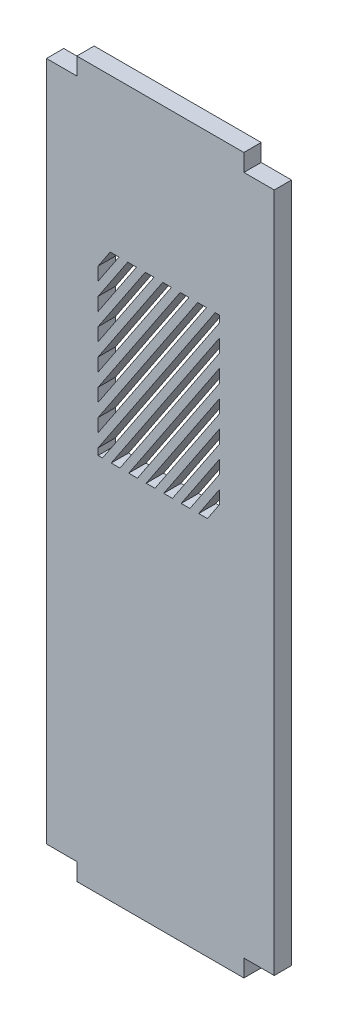
SolidWorks part; units mm, degrees
ref_plane "Front Plane" through (0, 0, 0) normal (0, 0, 1) x (1, 0, 0)
ref_plane "Top Plane" through (0, 0, 0) normal (0, 1, 0) x (1, 0, 0)
ref_plane "Right Plane" through (0, 0, 0) normal (1, 0, 0) x (0, 0, -1)
sketch "Sketch1" plane through (0, 0, 0) normal (0, 0, 1) x (1, 0, 0)
  line L1 (0, 0) -> (75, 0)
  line L2 (0, 0) -> (0, 235.4)
  line L3 (0, 235.4) -> (75, 235.4)
  line L4 (75, 0) -> (75, 235.4)
  dimension "D1" = 235.4
  dimension "D2" = 75
extrude "Boss-Extrude1" add sketch "Sketch1" along normal blind 5.7
sketch "Sketch2" plane through (0, 0, 0) normal (0, 0, -1) x (-1, 0, 0)
  line L2 (-75, 0) -> (-65, 0)
  line L3 (-75, 0) -> (-75, 5.7)
  line L4 (-75, 5.7) -> (-65, 5.7)
  line L6 (-65, 0) -> (-65, 5.7)
  line L7 (0, 0) -> (-10, 0)
  line L8 (0, 0) -> (0, 5.7)
  line L9 (0, 5.7) -> (-10, 5.7)
  line L12 (-10, 0) -> (-10, 5.7)
  line L13 (0, 235.4) -> (-10, 235.4)
  line L14 (0, 235.4) -> (0, 229.7)
  line L15 (0, 229.7) -> (-10, 229.7)
  line L16 (-10, 235.4) -> (-10, 229.7)
  line L17 (-75, 235.4) -> (-65, 235.4)
  line L18 (-75, 235.4) -> (-75, 229.7)
  line L19 (-75, 229.7) -> (-65, 229.7)
  line L20 (-65, 235.4) -> (-65, 229.7)
  dimension "D1" = 5.7
  dimension "D2" = 5.7
  dimension "D3" = 10
  dimension "D4" = 10
  dimension "D5" = 10
  dimension "D6" = 5.7
  dimension "D7" = 5.7
  dimension "D8" = 10
extrude "Cut-Extrude1" cut sketch "Sketch2" against normal blind 5.7
sketch "Sketch3" plane through (0, 0, 5.7) normal (0, 0, 1) x (1, 0, 0)
  line L1 (75, 5.7) -> (75, 229.7) construction
  line L39 (57, 185) -> (17, 125) construction
  line L40 (17, 185) -> (57, 185)
  line L41 (17, 185) -> (17, 125)
  line L42 (17, 125) -> (57, 125)
  line L43 (57, 185) -> (57, 125)
  line L44 (55.5578, 185) -> (17, 127.1633)
  line L45 (57, 182.8367) -> (18.4422, 125)
  line L46 (37, 155) -> (17, 155) construction
  line L47 (37, 155) -> (57, 155) construction
  line L48 (52.6778, 185) -> (17, 131.4833)
  line L49 (49.7978, 185) -> (17, 135.8033)
  line L50 (46.9178, 185) -> (17, 140.1233)
  line L51 (44.0378, 185) -> (17, 144.4433)
  line L52 (41.1578, 185) -> (17, 148.7633)
  line L53 (38.2778, 185) -> (17, 153.0833)
  line L54 (35.3978, 185) -> (17, 157.4033)
  line L55 (32.5178, 185) -> (17, 161.7233)
  line L56 (29.6378, 185) -> (17, 166.0433)
  line L57 (26.7578, 185) -> (17, 170.3633)
  line L58 (23.8778, 185) -> (17, 174.6833)
  line L59 (20.9978, 185) -> (17, 179.0033)
  line L60 (18.1178, 185) -> (17, 183.3233)
  line L61 (57, 178.5167) -> (21.3222, 125)
  line L62 (57, 174.1967) -> (24.2022, 125)
  line L63 (57, 169.8767) -> (27.0822, 125)
  line L64 (57, 165.5567) -> (29.9622, 125)
  line L65 (57, 161.2367) -> (32.8422, 125)
  line L66 (57, 156.9167) -> (35.7222, 125)
  line L67 (57, 152.5967) -> (38.6022, 125)
  line L68 (57, 148.2767) -> (41.4822, 125)
  line L69 (57, 143.9567) -> (44.3622, 125)
  line L70 (57, 139.6367) -> (47.2422, 125)
  line L71 (57, 135.3167) -> (50.1222, 125)
  line L72 (57, 130.9967) -> (53.0022, 125)
  line L73 (57, 126.6767) -> (55.8822, 125)
  line L74 (10, 0) -> (65, 0) construction
  point P79 (35.5578, 155)
  point P82 (38.4422, 155)
  dimension "D7" = 40
  dimension "D8" = 155
  dimension "D9" = 38
  dimension "D10" = 1.2
  dimension "D11" = 2.3963
  dimension "D12" = 2.3963
  dimension "D13" = 2.3963
  dimension "D14" = 2.3963
  dimension "D15" = 2.3963
  dimension "D16" = 2.3963
  dimension "D17" = 2.3963
  dimension "D18" = 2.3963
  dimension "D19" = 2.3963
  dimension "D20" = 2.3963
  dimension "D21" = 2.3963
  dimension "D22" = 2.3963
  dimension "D23" = 2.3963
  dimension "D24" = 2.3963
  dimension "D25" = 2.3963
  dimension "D26" = 2.3963
  dimension "D27" = 2.3963
  dimension "D28" = 2.3963
  dimension "D29" = 2.3963
  dimension "D30" = 2.3963
  dimension "D31" = 2.3963
  dimension "D32" = 2.3963
  dimension "D33" = 2.3963
  dimension "D34" = 2.3963
  dimension "D35" = 2.3963
  dimension "D36" = 2.3963
  dimension "D37" = 60
extrude "Cut-Extrude2" cut sketch "Sketch3" against normal blind 5.7 contours L45 L43 L40 L44 L41 L42 | L40 L49 L41 L48 | L40 L51 L41 L50 | L40 L53 L41 L52 | L40 L55 L41 L54 | L40 L57 L41 L56 | L40 L59 L41 L58 | L62 L43 L61 L42 | L64 L43 L63 L42 | L66 L43 L65 L42 | L68 L43 L67 L42 | L70 L43 L69 L42 | L72 L43 L71 L42
sketch "Sketch4" plane through (0, 0, 5.7) normal (0, 0, 1) x (1, 0, 0)
  circle A0 centre (64.3, 20.7) radius 1.5
  circle A1 centre (29.3, 20.7) radius 1.5
  circle A2 centre (64.3, 214.7) radius 1.5
  circle A3 centre (29.3, 214.7) radius 1.5
extrude "Cut-Extrude3" cut sketch "Sketch4" against normal blind 2 from offset 3.7
